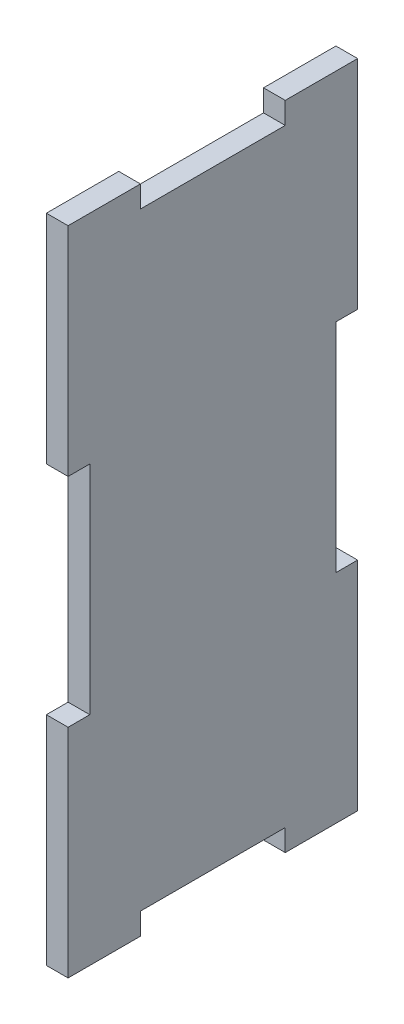
SolidWorks part; units mm, degrees
ref_plane "Plan de face" through (0, 0, 0) normal (0, 0, 1) x (1, 0, 0)
ref_plane "Plan de dessus" through (0, 0, 0) normal (0, 1, 0) x (1, 0, 0)
ref_plane "Plan de droite" through (0, 0, 0) normal (1, 0, 0) x (0, 0, -1)
sketch "Esquisse1" plane through (0, 0, 0) normal (1, 0, 0) x (0, 0, -1)
  line L0 (-7, 31.9236) -> (3, 31.9236)
  line L1 (-37, 31.9236) -> (-27, 31.9236)
  line L2 (-37, 31.9236) -> (-37, 1.9236)
  line L3 (-37, -58.0764) -> (-27, -58.0764)
  line L4 (3, 31.9236) -> (3, 1.9236)
  line L5 (3, -28.0764) -> (3, -58.0764)
  line L6 (-27, 31.9236) -> (-27, 28.9236)
  line L7 (-27, 28.9236) -> (-7, 28.9236)
  line L8 (-7, 31.9236) -> (-7, 28.9236)
  line L10 (-27, -58.0764) -> (-27, -55.0764)
  line L11 (-27, -55.0764) -> (-7, -55.0764)
  line L12 (-7, -58.0764) -> (-7, -55.0764)
  line L13 (3, 1.9236) -> (0, 1.9236)
  line L14 (-37, -28.0764) -> (-37, -58.0764)
  line L15 (3, -28.0764) -> (0, -28.0764)
  line L16 (0, 1.9236) -> (0, -28.0764)
  line L17 (-37, 1.9236) -> (-34, 1.9236)
  line L18 (-7, -58.0764) -> (3, -58.0764)
  line L19 (-37, -28.0764) -> (-34, -28.0764)
  line L20 (-34, 1.9236) -> (-34, -28.0764)
  dimension "D1" = 90
  dimension "D2" = 40
  dimension "D3" = 3
  dimension "D4" = 30
  dimension "D5" = 20
  dimension "D6" = 10
  dimension "D7" = 30
extrude "Boss.-Extru.1" add sketch "Esquisse1" along normal blind 3
